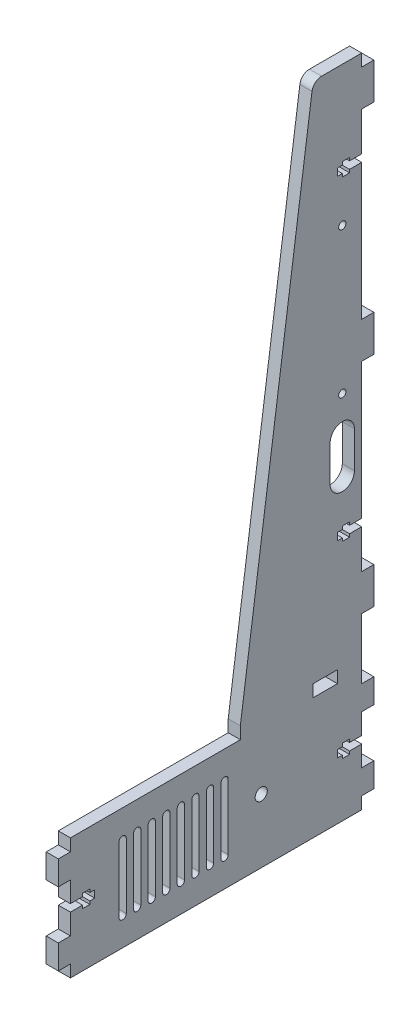
SolidWorks part; units mm, degrees
material "Maple"
ref_plane "Front Plane" through (0, 0, 0) normal (0, 0, 1) x (1, 0, 0)
ref_plane "Top Plane" through (0, 0, 0) normal (0, 1, 0) x (1, 0, 0)
ref_plane "Right Plane" through (0, 0, 0) normal (1, 0, 0) x (0, 0, -1)
sketch "Sketch1" plane through (0, 0, 0) normal (1, 0, 0) x (0, 0, -1)
  line L0 (-50, 50) -> (-50, 55)
  line L1 (-120, 50) -> (-50, 50)
  line L2 (-120, 50) -> (-120, 0)
  line L3 (-120, 0) -> (0, 0)
  line L4 (0, 50) -> (0, 0)
  line L5 (0, 270) -> (-20, 270)
  line L6 (-50, 55) -> (-20, 270)
  line L8 (0, 50) -> (-50, 50) construction
  line L9 (0, 270) -> (0, 55)
  line L10 (0, 55) -> (0, 50)
  line L11 (-10, 50) -> (-20, 50)
  line L12 (-10, 50) -> (-10, 55)
  line L13 (-10, 55) -> (-20, 55)
  line L14 (-20, 50) -> (-20, 55)
  point P4 (0, 52.5)
  dimension "D3" = 220
  dimension "D4" = 50
  dimension "D8" = 10
  dimension "D1" = 120
  dimension "D2" = 50
  dimension "D5" = 20
  dimension "D6" = 5
  dimension "D7" = 10
extrude "Boss-Extrude1" add sketch "Sketch1" along normal blind 5
sketch "Sketch2" plane through (5, 0, 0) normal (1, 0, 0) x (0, 0, -1)
  line L0 (-120, 50) -> (-120, 0) construction
  line L1 (-120, 5) -> (-125, 5)
  line L2 (-120, 5) -> (-120, 15)
  line L3 (-120, 15) -> (-125, 15)
  line L4 (-125, 5) -> (-125, 15)
  line L5 (-120, 45) -> (-125, 45)
  line L6 (-120, 45) -> (-120, 35)
  line L7 (-120, 35) -> (-125, 35)
  line L8 (-125, 45) -> (-125, 35)
  line L9 (-50, 50) -> (-120, 50) construction
  line L10 (-50, 50) -> (-120, 50) construction
  line L11 (0, 0) -> (0, 270) construction
  line L12 (0, 265) -> (5, 265)
  line L13 (0, 265) -> (0, 250)
  line L14 (-60, 50) -> (-60, 0) construction
  line L15 (-120, 0) -> (0, 0) construction
  line L16 (0, 250) -> (5, 250)
  line L17 (5, 265) -> (5, 250)
  line L19 (0, 70) -> (5, 70)
  line L20 (5, 45) -> (5, 35)
  line L21 (0, 35) -> (5, 35)
  line L22 (0, 45) -> (0, 35)
  line L23 (0, 45) -> (5, 45)
  line L24 (5, 5) -> (5, 15)
  line L25 (0, 15) -> (5, 15)
  line L26 (0, 5) -> (0, 15)
  line L27 (0, 5) -> (5, 5)
  line L28 (0, 70) -> (0, 85)
  line L29 (0, 85) -> (5, 85)
  line L30 (5, 70) -> (5, 85)
  line L31 (0, 175) -> (5, 175)
  line L32 (0, 175) -> (0, 160)
  line L33 (0, 160) -> (5, 160)
  line L34 (5, 175) -> (5, 160)
  dimension "D1" = 5
  dimension "D2" = 10
  dimension "D3" = 10
  dimension "D4" = 15
  dimension "D5" = 70
  dimension "D6" = 5
  dimension "D7" = 5
  dimension "D8" = 180
  dimension "D9" = 90
extrude "Boss-Extrude2" add sketch "Sketch2" against normal up to surface (5 mm away) up to face at (0, 99.2857, 51.4286)
sketch "Sketch3" plane through (5, 0, 0) normal (1, 0, 0) x (0, 0, -1)
  line L0 (0, 0) -> (0, 5) construction
  line L1 (0, 26.5) -> (-5, 26.5)
  line L2 (-5, 26.5) -> (-5, 27.75)
  line L3 (-5, 27.75) -> (-8, 27.75)
  line L4 (-8, 27.75) -> (-8, 26.5)
  line L5 (-8, 26.5) -> (-10, 26.5)
  line L6 (-10, 26.5) -> (-10, 23.5)
  line L7 (-10, 23.5) -> (-8, 23.5)
  line L8 (-8, 23.5) -> (-8, 22.25)
  line L9 (-8, 22.25) -> (-5, 22.25)
  line L10 (-5, 22.25) -> (-5, 23.5)
  line L11 (-5, 23.5) -> (0, 23.5)
  line L12 (0, 23.5) -> (0, 26.5)
  line L13 (0, 104) -> (-5, 104)
  line L14 (-5, 104) -> (-5, 105.25)
  line L15 (-5, 105.25) -> (-8, 105.25)
  line L16 (-8, 105.25) -> (-8, 104)
  line L17 (-8, 104) -> (-10, 104)
  line L18 (-10, 104) -> (-10, 101)
  line L19 (-10, 101) -> (-8, 101)
  line L20 (-8, 101) -> (-8, 99.75)
  line L21 (-8, 99.75) -> (-5, 99.75)
  line L22 (-5, 99.75) -> (-5, 101)
  line L23 (-5, 101) -> (0, 101)
  line L24 (0, 101) -> (0, 104)
  line L25 (0, 234) -> (-5, 234)
  line L26 (-5, 234) -> (-5, 235.25)
  line L27 (-5, 235.25) -> (-8, 235.25)
  line L28 (-8, 235.25) -> (-8, 234)
  line L29 (-8, 234) -> (-10, 234)
  line L30 (-10, 234) -> (-10, 231)
  line L31 (-10, 231) -> (-8, 231)
  line L32 (-8, 231) -> (-8, 229.75)
  line L33 (-8, 229.75) -> (-5, 229.75)
  line L34 (-5, 229.75) -> (-5, 231)
  line L35 (-5, 231) -> (0, 231)
  line L36 (0, 231) -> (0, 234)
  line L37 (0, 15) -> (0, 35) construction
  line L38 (0, 85) -> (0, 160) construction
  line L39 (0, 175) -> (0, 250) construction
  line L40 (5, 70) -> (5, 85) construction
  line L41 (5, 250) -> (5, 265) construction
  line L42 (-60, 0) -> (-60, 50) construction
  line L43 (-120, 0) -> (0, 0) construction
  line L44 (-50, 50) -> (-120, 50) construction
  line L45 (-120, 23.5) -> (-120, 26.5)
  line L46 (-115, 23.5) -> (-120, 23.5)
  line L47 (-115, 22.25) -> (-115, 23.5)
  line L48 (-112, 22.25) -> (-115, 22.25)
  line L49 (-112, 23.5) -> (-112, 22.25)
  line L50 (-110, 23.5) -> (-112, 23.5)
  line L51 (-110, 26.5) -> (-110, 23.5)
  line L52 (-112, 26.5) -> (-110, 26.5)
  line L53 (-112, 27.75) -> (-112, 26.5)
  line L54 (-115, 27.75) -> (-112, 27.75)
  line L55 (-115, 26.5) -> (-115, 27.75)
  line L56 (-120, 26.5) -> (-115, 26.5)
  line L57 (-8, 152.5) -> (-8, 212.5) construction
  line L58 (-8, 137.5) -> (-8, 122.5) construction
  line L59 (-3, 137.5) -> (-3, 122.5)
  line L60 (-13, 137.5) -> (-13, 122.5)
  circle A0 centre (-41.4, 26.3) radius 2.5
  circle A1 centre (-8, 212.5) radius 1.5
  circle A2 centre (-8, 152.5) radius 1.5
  arc A3 (-3, 137.5) -> (-13, 137.5) centre (-8, 137.5) ccw
  arc A4 (-13, 122.5) -> (-3, 122.5) centre (-8, 122.5) ccw
  point P7 (0, 25)
  point P18 (-2.5, 23.5)
  point P21 (0, 102.5)
  point P32 (-2.5, 101)
  point P35 (0, 232.5)
  point P46 (-2.5, 231)
  point P58 (5, 77.5)
  point P61 (5, 257.5)
  point P81 (-8, 130)
  dimension "D2" = 5
  dimension "D21" = 3
  dimension "D1" = 41.4
  dimension "D3" = 26.3
  dimension "D4" = 3
  dimension "D5" = 3
  dimension "D6" = 2
  dimension "D7" = 5
  dimension "D8" = 5.5
  dimension "D9" = 3
  dimension "D10" = 3
  dimension "D11" = 2
  dimension "D12" = 5
  dimension "D13" = 5.5
  dimension "D14" = 3
  dimension "D15" = 3
  dimension "D16" = 2
  dimension "D17" = 5
  dimension "D18" = 5.5
  dimension "D19" = 25
  dimension "D20" = 25
  dimension "D22" = 60
  dimension "D23" = 8
  dimension "D24" = 20
  dimension "D25" = 15
  dimension "D26" = 10
  dimension "D27" = 15
extrude "Cut-Extrude1" cut sketch "Sketch3" against normal through all
sketch "Sketch4" plane through (5, 0, 0) normal (1, 0, 0) x (0, 0, -1)
  line L0 (-50, 50) -> (-120, 50) construction
  line L1 (-100, 40) -> (-51.4, 40) construction
  line L2 (-100, 40) -> (-100, 10) construction
  line L3 (-100, 10) -> (-51.4, 10) construction
  line L4 (-51.4, 40) -> (-51.4, 10) construction
  line L5 (-110, 23.5) -> (-110, 26.5) construction
  line L6 (-120, 0) -> (0, 0) construction
  line L7 (-98.5, 38.5) -> (-98.5, 11.5) construction
  line L8 (-97, 38.5) -> (-97, 11.5)
  line L9 (-100, 38.5) -> (-100, 11.5)
  line L10 (-94, 40) -> (-94, 10) construction
  line L11 (-92.5, 38.5) -> (-92.5, 11.5) construction
  line L12 (-91, 38.5) -> (-91, 11.5)
  line L13 (-94, 38.5) -> (-94, 11.5)
  line L14 (-88, 40) -> (-88, 10) construction
  line L15 (-86.5, 38.5) -> (-86.5, 11.5) construction
  line L16 (-85, 38.5) -> (-85, 11.5)
  line L17 (-88, 38.5) -> (-88, 11.5)
  line L18 (-82, 40) -> (-82, 10) construction
  line L19 (-80.5, 38.5) -> (-80.5, 11.5) construction
  line L20 (-79, 38.5) -> (-79, 11.5)
  line L21 (-82, 38.5) -> (-82, 11.5)
  line L22 (-76, 40) -> (-76, 10) construction
  line L23 (-74.5, 38.5) -> (-74.5, 11.5) construction
  line L24 (-73, 38.5) -> (-73, 11.5)
  line L25 (-76, 38.5) -> (-76, 11.5)
  line L26 (-70, 40) -> (-70, 10) construction
  line L27 (-68.5, 38.5) -> (-68.5, 11.5) construction
  line L28 (-67, 38.5) -> (-67, 11.5)
  line L29 (-70, 38.5) -> (-70, 11.5)
  line L30 (-64, 40) -> (-64, 10) construction
  line L31 (-62.5, 38.5) -> (-62.5, 11.5) construction
  line L32 (-61, 38.5) -> (-61, 11.5)
  line L33 (-64, 38.5) -> (-64, 11.5)
  line L34 (-58, 40) -> (-58, 10) construction
  line L35 (-56.5, 38.5) -> (-56.5, 11.5) construction
  line L36 (-55, 38.5) -> (-55, 11.5)
  line L37 (-58, 38.5) -> (-58, 11.5)
  circle A0 centre (-41.4, 26.3) radius 2.5 construction
  arc A1 (-97, 38.5) -> (-100, 38.5) centre (-98.5, 38.5) ccw
  arc A2 (-100, 11.5) -> (-97, 11.5) centre (-98.5, 11.5) ccw
  arc A3 (-91, 38.5) -> (-94, 38.5) centre (-92.5, 38.5) ccw
  arc A4 (-94, 11.5) -> (-91, 11.5) centre (-92.5, 11.5) ccw
  arc A5 (-85, 38.5) -> (-88, 38.5) centre (-86.5, 38.5) ccw
  arc A6 (-88, 11.5) -> (-85, 11.5) centre (-86.5, 11.5) ccw
  arc A7 (-79, 38.5) -> (-82, 38.5) centre (-80.5, 38.5) ccw
  arc A8 (-82, 11.5) -> (-79, 11.5) centre (-80.5, 11.5) ccw
  arc A9 (-73, 38.5) -> (-76, 38.5) centre (-74.5, 38.5) ccw
  arc A10 (-76, 11.5) -> (-73, 11.5) centre (-74.5, 11.5) ccw
  arc A11 (-67, 38.5) -> (-70, 38.5) centre (-68.5, 38.5) ccw
  arc A12 (-70, 11.5) -> (-67, 11.5) centre (-68.5, 11.5) ccw
  arc A13 (-61, 38.5) -> (-64, 38.5) centre (-62.5, 38.5) ccw
  arc A14 (-64, 11.5) -> (-61, 11.5) centre (-62.5, 11.5) ccw
  arc A15 (-55, 38.5) -> (-58, 38.5) centre (-56.5, 38.5) ccw
  arc A16 (-58, 11.5) -> (-55, 11.5) centre (-56.5, 11.5) ccw
  point P8 (-110, 25)
  point P15 (-98.5, 25)
  point P20 (-98.5, 10)
  point P21 (-98.5, 40)
  point P28 (-92.5, 25)
  point P37 (-86.5, 25)
  point P46 (-80.5, 25)
  point P55 (-74.5, 25)
  point P64 (-68.5, 25)
  point P73 (-62.5, 25)
  point P82 (-56.5, 25)
  dimension "D1" = 10
  dimension "D2" = 10
  dimension "D3" = 10
  dimension "D4" = 10
  dimension "D5" = 3
  dimension "D6" = 8
extrude "Cut-Extrude2" cut sketch "Sketch4" against normal through all
fillet "Fillet1" radius 4 1 edges at (2.5, 270, 20)
